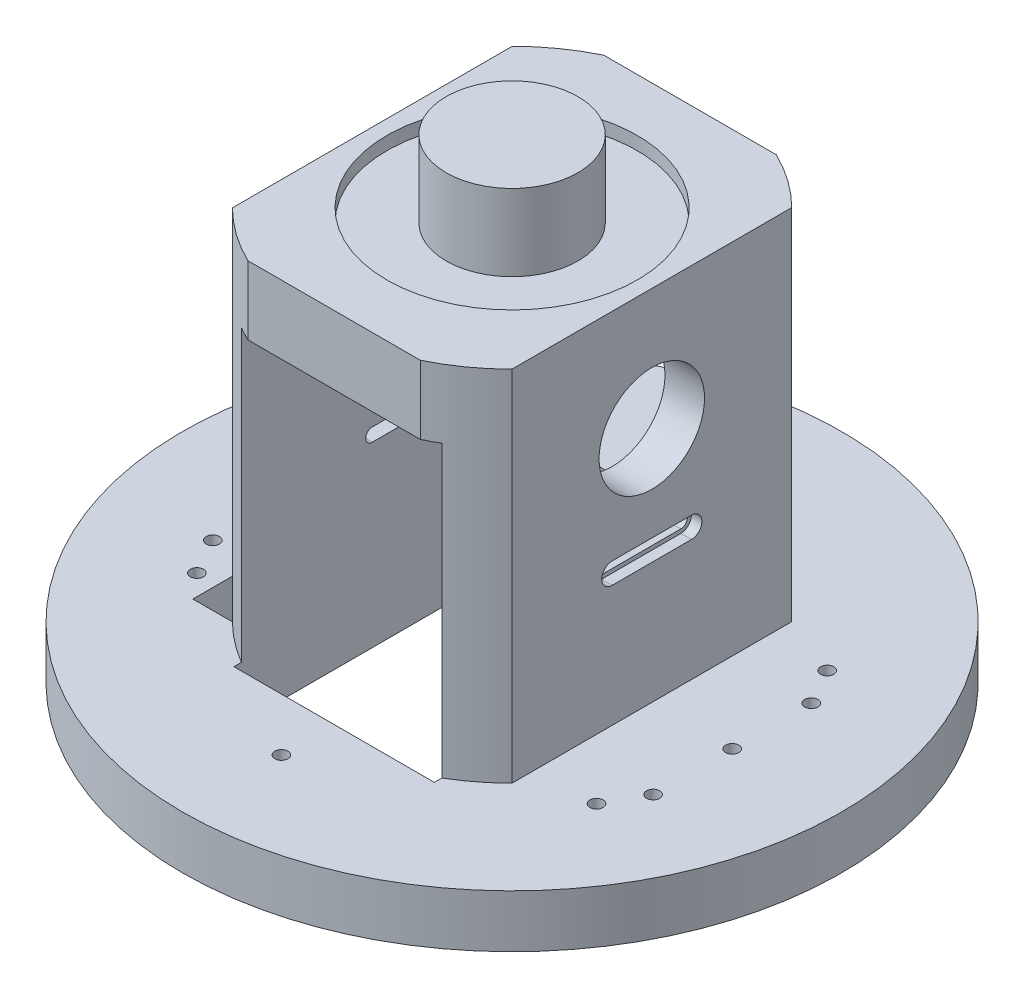
SolidWorks part; units mm, degrees
ref_plane "Front Plane" through (0, 0, 0) normal (0, 0, 1) x (1, 0, 0)
ref_plane "Top Plane" through (0, 0, 0) normal (0, 1, 0) x (1, 0, 0)
ref_plane "Right Plane" through (0, 0, 0) normal (1, 0, 0) x (0, 0, -1)
sketch "Sketch1" plane through (0, 0, 0) normal (0, 1, 0) x (1, 0, 0)
  circle A0 centre (0, 0) radius 125
  dimension "D1" = 250
extrude "Boss-Extrude1" add sketch "Sketch1" along normal blind 20
sketch "Sketch2" plane through (0, 20, 0) normal (0, 1, 0) x (1, 0, 0)
  line L1 (-53, 67.5) -> (53, 67.5)
  line L2 (-53, 67.5) -> (-53, -67.5)
  line L3 (-53, -67.5) -> (53, -67.5)
  line L4 (53, 67.5) -> (53, -67.5)
  line L5 (-53, 67.5) -> (53, -67.5) construction
  line L6 (-53, -67.5) -> (53, 67.5) construction
  point P0 (0, 0)
  dimension "D1" = 106
  dimension "D2" = 135
extrude "Boss-Extrude2" add sketch "Sketch2" along normal blind 160
sketch "Sketch5" plane through (53, 0, 0) normal (1, 0, 0) x (0, 0, -1)
  circle A0 centre (0, 110) radius 67.5 construction
  circle A1 centre (0, 110) radius 20
  dimension "D1" = 135
  dimension "D3" = 40
  dimension "D2" = 110
extrude "Cut-Extrude2" cut sketch "Sketch5" against normal through all
sketch "Sketch6" plane through (0, 0, 0) normal (0, -1, 0) x (1, 0, 0)
  line L1 (-38, 67.5) -> (38, 67.5)
  line L2 (-38, 67.5) -> (-38, -67.5)
  line L3 (-38, -67.5) -> (38, -67.5)
  line L4 (38, 67.5) -> (38, -67.5)
  line L5 (-38, 67.5) -> (38, -67.5) construction
  line L6 (-38, -67.5) -> (38, 67.5) construction
  point P0 (0, 0)
  dimension "D1" = 135
  dimension "D2" = 76
extrude "Cut-Extrude3" cut sketch "Sketch6" against normal blind 130
sketch "Sketch7" plane through (0, 180, 0) normal (0, 1, 0) x (1, 0, 0)
  line L0 (53, -67.5) -> (53, 67.5) construction
  line L1 (-53, 67.5) -> (53, 67.5)
  line L2 (-53, 67.5) -> (-53, -67.5)
  line L3 (-53, -67.5) -> (53, -67.5)
  line L4 (53, 67.5) -> (53, -67.5)
  line L5 (-53, 67.5) -> (53, -67.5) construction
  line L6 (-53, -67.5) -> (53, 67.5) construction
  circle A0 centre (0, 0) radius 47.5 construction
  circle A1 centre (0, 0) radius 25
  dimension "D1" = 95
  dimension "D2" = 50
  dimension "D3" = 135
extrude "Cut-Extrude5" cut sketch "Sketch7" against normal blind 29
sketch "Sketch10" plane through (0, 151, 0) normal (0, 1, 0) x (1, 0, 0)
  line L1 (-53, 67.5) -> (53, 67.5)
  line L2 (-53, 67.5) -> (-53, -67.5)
  line L3 (-53, -67.5) -> (53, -67.5)
  line L4 (53, 67.5) -> (53, -67.5)
  line L5 (-53, 67.5) -> (53, -67.5) construction
  line L6 (-53, -67.5) -> (53, 67.5) construction
  circle A0 centre (0, 0) radius 47.5
  dimension "D1" = 95
extrude "Boss-Extrude4" add sketch "Sketch10" along normal blind 5
sketch "Sketch11" plane through (0, 0, 0) normal (0, -1, 0) x (-1, 0, 0)
  line L0 (0, 125) -> (0, -125) construction
  line L1 (83.5029, 0) -> (0, 0) construction
  line L2 (0, 0) -> (-83.5029, 0) construction
  circle A0 centre (0, 0) radius 125 construction
  circle A1 centre (83.5029, 0) radius 2.5
  circle A2 centre (-83.5029, 0) radius 2.5
  circle A3 centre (83.5029, -30) radius 2.5
  circle A4 centre (83.5029, 30) radius 2.5
  circle A5 centre (-83.5029, 30) radius 2.5
  circle A6 centre (-83.5029, -30) radius 2.5
  dimension "D1" = 5
  dimension "D2" = 5
  dimension "D3" = 167.0059
  dimension "D4" = 30
  dimension "D5" = 30
extrude "Cut-Extrude6" cut sketch "Sketch11" against normal through all
sketch "Sketch12" plane through (0, 0, 0) normal (0, -1, 0) x (-1, 0, 0)
  circle A0 centre (0, 0) radius 87.5 construction
  circle A2 centre (0, 87.5) radius 2.5
  circle A10 centre (75.7772, 43.75) radius 2.5
  circle A11 centre (75.7772, -43.75) radius 2.5
  circle A12 centre (0, -87.5) radius 2.5
  circle A13 centre (-75.7772, -43.75) radius 2.5
  circle A14 centre (-75.7772, 43.75) radius 2.5
  point P17 (0, 0)
  point P21 (0, 0)
  dimension "D1" = 175
  dimension "D2" = 5
  dimension "D3" = 6
extrude "Cut-Extrude7" cut sketch "Sketch12" against normal through all
sketch "Sketch13" plane through (0, 0, 0) normal (0, -1, 0) x (-1, 0, 0)
  circle A0 centre (0, -87.5) radius 5
  circle A1 centre (-75.7772, -43.75) radius 5
  circle A2 centre (-75.7772, 43.75) radius 5
  circle A5 centre (0, 87.5) radius 5
  circle A6 centre (75.7772, 43.75) radius 5
  circle A7 centre (75.7772, -43.75) radius 5
  dimension "D1" = 10
extrude "Cut-Extrude8" cut sketch "Sketch13" against normal blind 5
sketch "Sketch14" plane through (0, 156, 0) normal (0, 1, 0) x (1, 0, 0)
  circle A0 centre (0, 0) radius 75
  circle A1 centre (0, 0) radius 94.4551
  dimension "D1" = 150
extrude "Cut-Extrude10" cut sketch "Sketch14" against normal up to surface (136 mm away) up to face at (75.7772, 20, 46.25)
sketch "Sketch15" plane through (0, 20, 0) normal (0, 1, 0) x (1, 0, 0)
  line L5 (-53, 53.066) -> (-68, 53.066)
  line L6 (-53, 53.066) -> (-53, -53.066)
  line L7 (-53, -53.066) -> (-68, -53.066)
  line L8 (-68, 53.066) -> (-68, -53.066)
  dimension "D1" = 15
extrude "Cut-Extrude11" cut sketch "Sketch15" against normal blind 20
sketch "Sketch16" plane through (-38, 0, 0) normal (1, 0, 0) x (0, 0, -1)
  line L0 (-15, 70) -> (15, 70) construction
  line L1 (-15, 72.5) -> (15, 72.5)
  line L2 (-15, 67.5) -> (15, 67.5)
  line L3 (0, 130) -> (64.6607, 130) construction
  arc A0 (-15, 72.5) -> (-15, 67.5) centre (-15, 70) ccw
  arc A1 (15, 67.5) -> (15, 72.5) centre (15, 70) ccw
  point P2 (0, 70)
  dimension "D2" = 2.5
  dimension "D1" = 30
  dimension "D3" = 60
extrude "Cut-Extrude12" cut sketch "Sketch16" against normal through all both and the other way through all
sketch "Sketch17" plane through (-53, 0, 0) normal (-1, 0, 0) x (0, 0, 1)
  line L0 (-15, 70) -> (15, 70) construction
  line L1 (-15, 74) -> (15, 74)
  line L2 (-15, 66) -> (15, 66)
  arc A0 (-15, 74) -> (-15, 66) centre (-15, 70) ccw
  arc A1 (15, 66) -> (15, 74) centre (15, 70) ccw
  point P4 (0, 70)
  dimension "D1" = 4
extrude "Cut-Extrude13" cut sketch "Sketch17" against normal blind 4
mirror "Mirror1" about plane through (0, 0, 0) normal (1, 0, 0) of "Cut-Extrude13"
